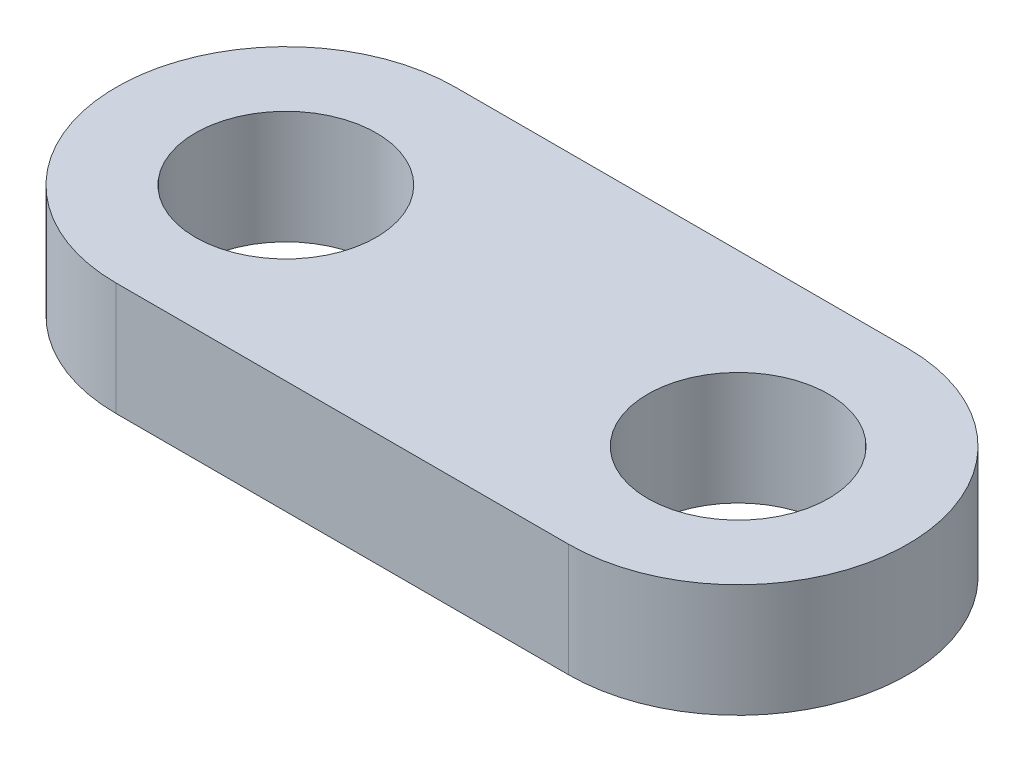
SolidWorks part; units mm, degrees
ref_plane "前视基准面" through (0, 0, 0) normal (0, 0, 1) x (1, 0, 0)
ref_plane "上视基准面" through (0, 0, 0) normal (0, 1, 0) x (1, 0, 0)
ref_plane "右视基准面" through (0, 0, 0) normal (1, 0, 0) x (0, 0, -1)
sketch "草图1" plane through (0, 0, 0) normal (0, 1, 0) x (1, 0, 0)
  line L0 (-10, 0) -> (10, 0) construction
  line L1 (-10, 7.5) -> (10, 7.5)
  line L2 (-10, -7.5) -> (10, -7.5)
  arc A0 (-10, 7.5) -> (-10, -7.5) centre (-10, 0) ccw
  arc A1 (10, -7.5) -> (10, 7.5) centre (10, 0) ccw
  circle A2 centre (-10, 0) radius 4
  circle A3 centre (10, 0) radius 4
  point P2 (0, 0)
  dimension "D1" = 7.5
  dimension "D3" = 8
  dimension "D4" = 8
  dimension "D2" = 20
extrude "凸台-拉伸1" add sketch "草图1" along normal blind 5
